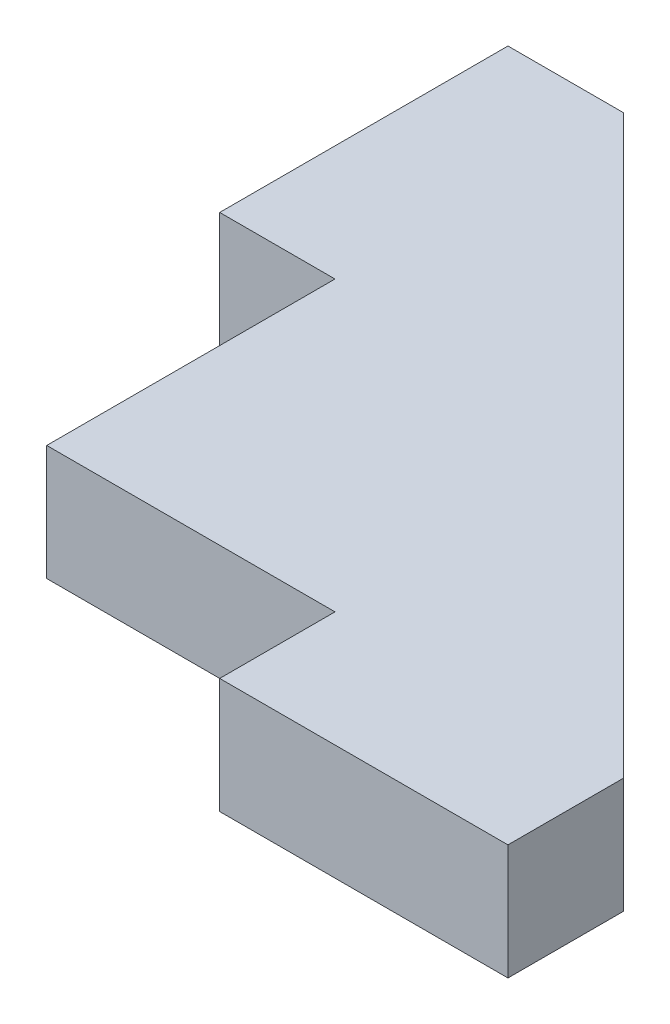
SolidWorks part; units mm, degrees
ref_plane "Front Plane" through (0, 0, 0) normal (0, 0, 1) x (1, 0, 0)
ref_plane "Top Plane" through (0, 0, 0) normal (0, 1, 0) x (1, 0, 0)
ref_plane "Right Plane" through (0, 0, 0) normal (1, 0, 0) x (0, 0, -1)
sketch "Sketch1" plane through (0, 0, 0) normal (0, 1, 0) x (1, 0, 0)
  line L0 (0, 0) -> (10, 0)
  line L1 (10, 0) -> (0, 10)
  line L2 (0, 10) -> (0, 0)
  line L4 (0, 10) -> (-2, 10)
  line L5 (0, 10) -> (0, 5)
  line L6 (0, 5) -> (-2, 5)
  line L7 (-2, 10) -> (-2, 5)
  line L8 (10, 0) -> (5, 0)
  line L9 (10, 0) -> (10, -2)
  line L10 (10, -2) -> (5, -2)
  line L11 (5, 0) -> (5, -2)
  dimension "D1" = 10
  dimension "D2" = 10
  dimension "D3" = 5
  dimension "D4" = 5
  dimension "D5" = 2
  dimension "D6" = 2
extrude "Boss-Extrude1" add sketch "Sketch1" along normal blind 2 contours L1 L2 L0 | L4 L7 L6 L2 | L0 L11 L10 L9
